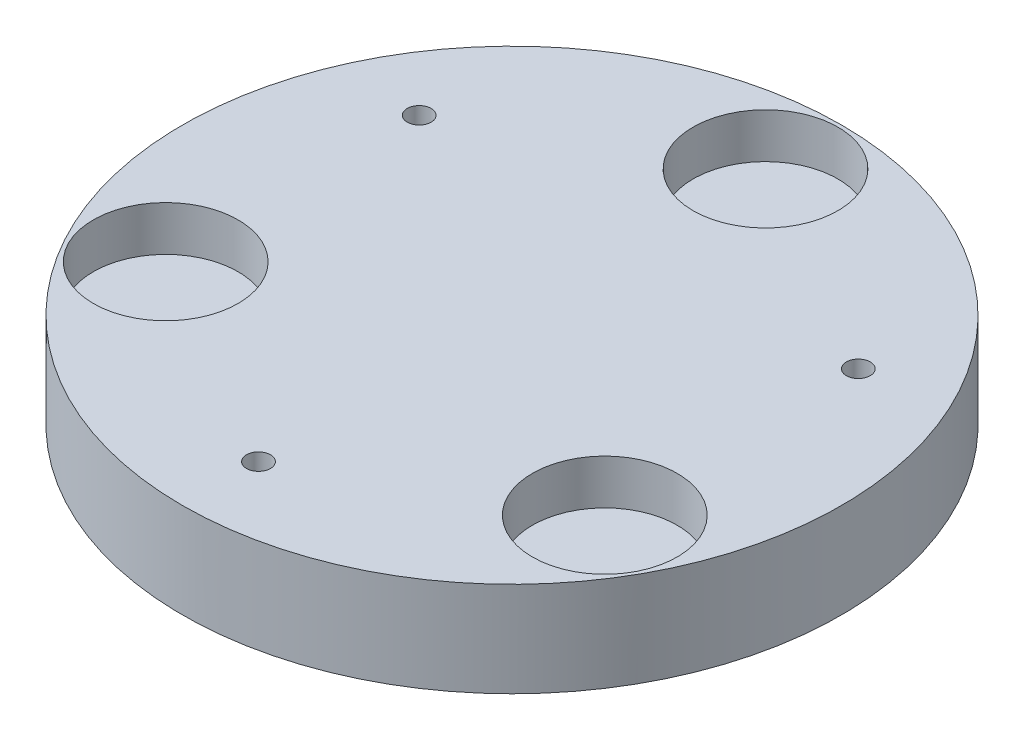
SolidWorks part; units mm, degrees
ref_plane "Plan de face" through (0, 0, 0) normal (0, 0, 1) x (1, 0, 0)
ref_plane "Plan de dessus" through (0, 0, 0) normal (0, 1, 0) x (1, 0, 0)
ref_plane "Plan de droite" through (0, 0, 0) normal (1, 0, 0) x (0, 0, -1)
sketch "Esquisse1" plane through (0, 0, 0) normal (0, 0, 1) x (1, 0, 0)
  line L0 (-96, 155.6058) -> (-88, 155.6058) construction
  line L1 (-88, 155.6058) -> (-88, 150.6058) construction
  line L2 (-88, 150.6058) -> (-80.5, 150.6058) construction
  line L3 (-96, 155.6058) -> (-96, 145.6058) construction
  line L4 (-96, 145.6058) -> (-78.3223, 127.9282) construction
  line L5 (-78.3223, 127.9282) -> (-78.3223, 132.9282) construction
  line L6 (-78.3223, 132.9282) -> (-80.5, 135.1058) construction
  line L7 (-80.5, 150.6058) -> (-80.5, 135.1058) construction
  line L8 (-80.5, 155.6058) -> (-80.5, 150.6058) construction
  line L9 (0, 0) -> (0, 200.3396) construction
  line L10 (0, 158.1207) -> (-80.3109, 158.1207) construction
  line L11 (0, 161.1207) -> (0, 158.1207) construction
  line L12 (0, 161.1207) -> (-80.3109, 161.1207) construction
  line L13 (-80.3109, 158.1207) -> (-80.3109, 161.1207) construction
  line L14 (-45.5, 158.1207) -> (-45.5, 145.0302)
  line L15 (96, 155.6058) -> (80.5, 155.6058) construction
  line L16 (-45.5, 158.1207) -> (0, 158.1207)
  line L17 (0, 158.1207) -> (0, 152)
  circle A0 centre (0, 0) radius 150 construction
  arc A1 (-96, 155.6058) -> (96, 155.6058) centre (0, 155.6058) cw construction
  arc A2 (-80.5, 155.6058) -> (80.5, 155.6058) centre (0, 155.6058) cw construction
  circle A3 centre (-60.5, 148.1207) radius 10 construction
  arc A4 (0, 152) -> (-45.5, 145.0302) centre (0, 0) ccw
  dimension "D1" = 300
  dimension "D2" = 8
  dimension "D3" = 10
  dimension "D5" = 5
  dimension "D4" = 135
  dimension "D10" = 20
  dimension "D11" = 20
  dimension "D12" = 3
  dimension "D15" = 152
  dimension "D9" = 15.5
  dimension "D8" = 96
  dimension "D14" = 152
  dimension "D13" = 15
  dimension "D6" = 25
  dimension "D7" = 5
revolve "Révolution1" add sketch "Esquisse1" angle 360 about L9
ref_plane "Plan2" through (0, 158.1207, 0) normal (0, 1, 0) x (1, 0, 0)
sketch "Esquisse11" plane through (0, 158.1207, 0) normal (0, 1, 0) x (1, 0, 0)
  circle A0 centre (0, 0) radius 35 construction
  circle A1 centre (0, 35) radius 10
  dimension "D1" = 70
  dimension "D2" = 20
extrude "Enlèv. mat.-Extru.4" cut sketch "Esquisse11" against normal blind 6.2
sketch "Esquisse12" plane through (0, 158.1207, 0) normal (0, 1, 0) x (1, 0, 0)
  circle A0 centre (0, 0) radius 35 construction
  circle A1 centre (-30.3109, 17.5) radius 1.65
  circle A2 centre (0, 35) radius 10 construction
  dimension "D1" = 3.3
  dimension "D2" = 70
  dimension "D3" = 17.5
extrude "Enlèv. mat.-Extru.5" cut sketch "Esquisse12" against normal through all
ref_plane "Plan3" through (0, 147.1207, 0) normal (0, 1, 0) x (1, 0, 0)
sketch "Esquisse14" plane through (0, 147.1207, 0) normal (0, 1, 0) x (1, 0, 0)
  circle A0 centre (-30.3109, 17.5) radius 2.85
  dimension "D1" = 5.7
extrude "Enlèv. mat.-Extru.8" cut sketch "Esquisse14" along normal blind 3.6
pattern_circular "Répétition circulaire7" count 3 every 120 about axis through (0, 0, 0) along (0, 1, 0) of "Enlèv. mat.-Extru.8", "Enlèv. mat.-Extru.5", "Enlèv. mat.-Extru.4"
